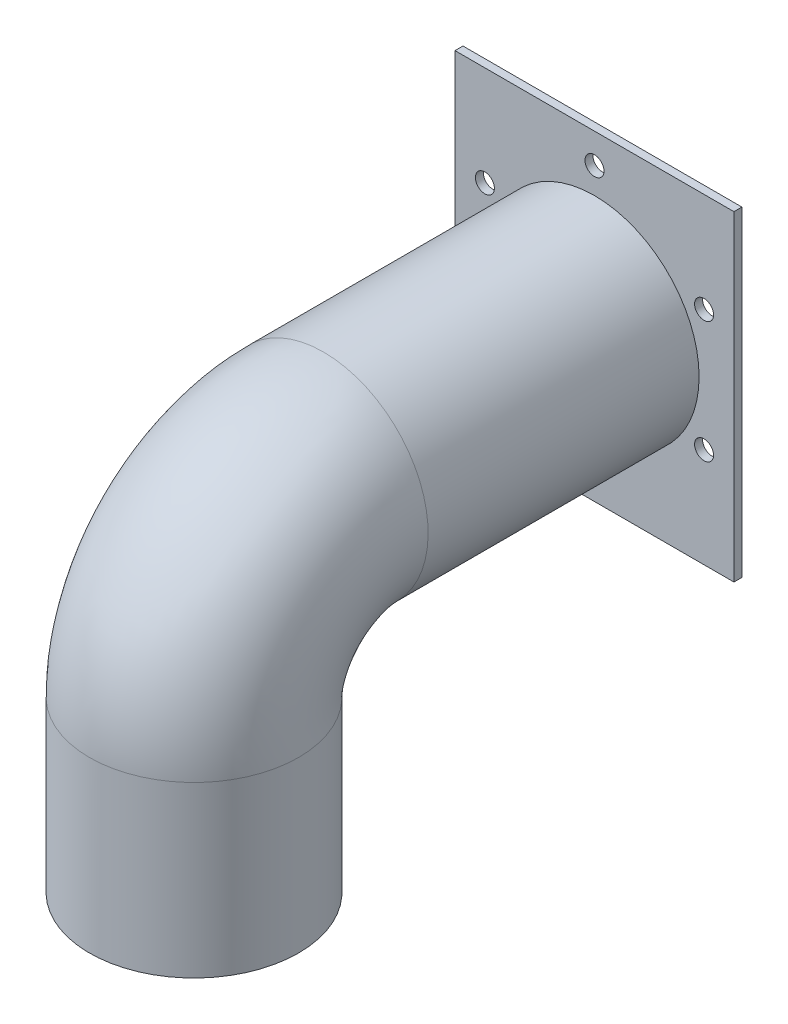
SolidWorks part; units mm, degrees
ref_plane "Alzado" through (0, 0, 0) normal (0, 0, 1) x (1, 0, 0)
ref_plane "Planta" through (0, 0, 0) normal (0, 1, 0) x (1, 0, 0)
ref_plane "Vista lateral" through (0, 0, 0) normal (1, 0, 0) x (0, 0, -1)
sketch "Croquis1" plane through (0, 0, 0) normal (0, 0, 1) x (1, 0, 0)
  circle A0 centre (0, 0) radius 105
  dimension "D1" = 210
extrude "Saliente-Extruir1" add sketch "Croquis1" along normal blind 10
sketch3d "Croquis3D1"
  line L0 (0, 0, 10) -> (0, 0, 280)
  line L1 (0, 0, 10) -> (0, 0, 0) construction
  line L2 (0, -130, 410) -> (0, -300, 410)
  arc A0 (0, 0, 280) -> (0, -130, 410) centre (0, -130, 280) ccw
  point P7 (0, 0, 410)
  point P8 (130, -130, 280)
  dimension "D3" = 130
  dimension "D1" = 400
  dimension "D2" = 300
sketch "Croquis2" plane through (0, 0, 10) normal (0, 0, 1) x (1, 0, 0)
  circle A0 centre (0, 0) radius 105
  dimension "D1" = 210
sweep "Barrer1" add profiles "Croquis2" path "Croquis3D1"
sketch "Croquis3" plane through (0, 0, 0) normal (0, 0, -1) x (-1, 0, 0)
  line L1 (-140, -161) -> (140, -161)
  line L2 (-140, -161) -> (-140, 161)
  line L3 (-140, 161) -> (140, 161)
  line L4 (140, -161) -> (140, 161)
  line L5 (-140, -161) -> (140, 161) construction
  line L6 (-140, 161) -> (140, -161) construction
  point P0 (0, 0)
  dimension "D1" = 280
  dimension "D2" = 322
extrude "Saliente-Extruir2" add sketch "Croquis3" against normal blind 8
sketch "Croquis6" plane through (0, 0, 0) normal (0, 0, -1) x (-1, 0, 0)
  line L0 (0, 161) -> (0, 131) construction
  line L1 (140, 161) -> (-140, 161) construction
  line L2 (-140, 61) -> (-110, 61) construction
  line L3 (-140, 161) -> (-140, -161) construction
  line L4 (140, 61) -> (110, 61) construction
  line L5 (-140, 0) -> (0, 0) construction
  line L6 (140, -61) -> (110, -61) construction
  line L7 (-140, -61) -> (-110, -61) construction
  line L8 (0, -161) -> (0, -131) construction
  circle A0 centre (0, 131) radius 9.525
  circle A1 centre (-110, 61) radius 9.525
  circle A2 centre (110, 61) radius 9.525
  circle A3 centre (110, -61) radius 9.525
  circle A4 centre (-110, -61) radius 9.525
  circle A5 centre (0, -131) radius 9.525
  dimension "D2" = 19.05
  dimension "D4" = 19.05
  dimension "D5" = 100
  dimension "D1" = 30
  dimension "D3" = 30
extrude "Cortar-Extruir1" cut sketch "Croquis6" against normal blind 10
